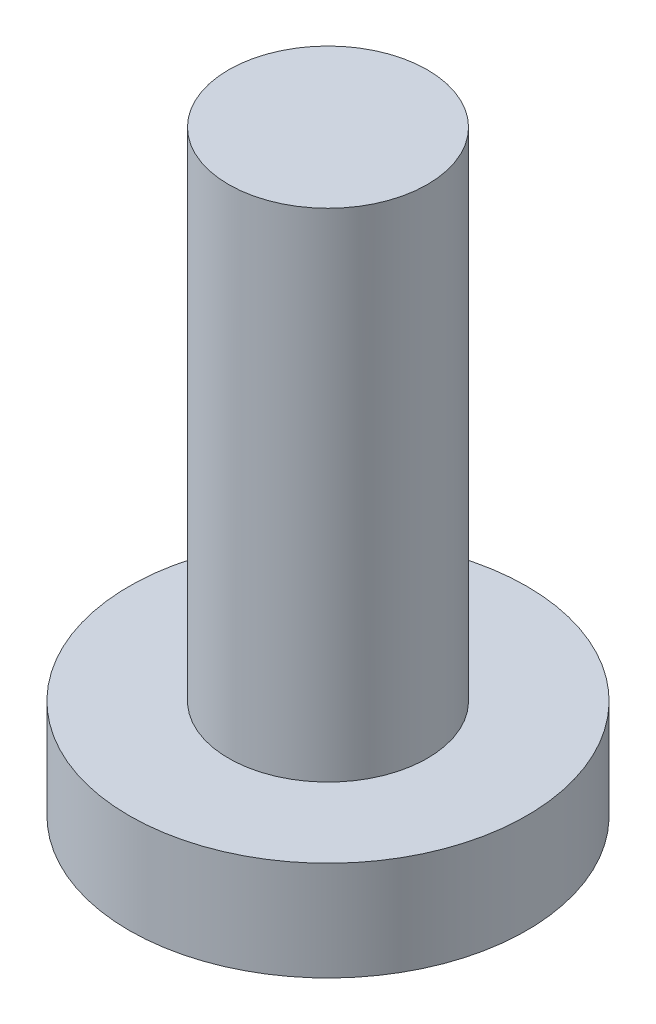
SolidWorks part; units mm, degrees
ref_plane "Front Plane" through (0, 0, 0) normal (0, 0, 1) x (1, 0, 0)
ref_plane "Top Plane" through (0, 0, 0) normal (0, 1, 0) x (1, 0, 0)
ref_plane "Right Plane" through (0, 0, 0) normal (1, 0, 0) x (0, 0, -1)
sketch "Sketch2" plane through (0, 0, 0) normal (0, 1, 0) x (1, 0, 0)
  circle A0 centre (0, 0) radius 1
  dimension "D1" = 2
extrude "Boss-Extrude1" add sketch "Sketch2" along normal blind 5
sketch "Sketch3" plane through (0, 0, 0) normal (0, -1, 0) x (1, 0, 0)
  circle A0 centre (0, 0) radius 2
  dimension "D1" = 4
extrude "Boss-Extrude2" add sketch "Sketch3" along normal blind 1
